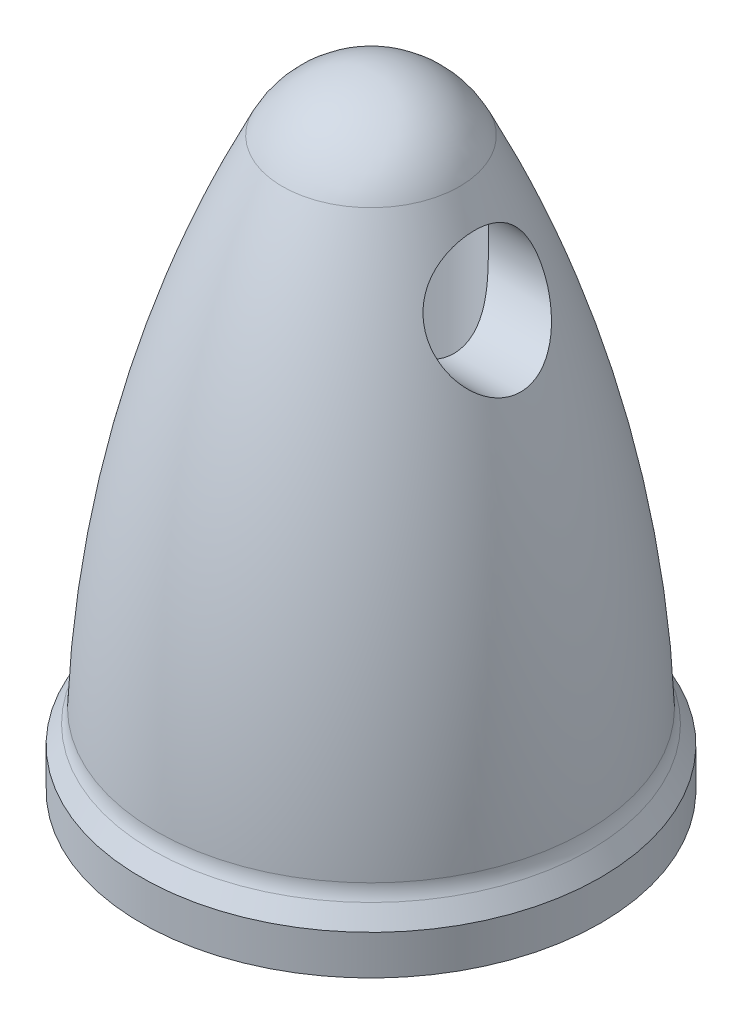
SolidWorks part; units mm, degrees
material "6061 Alloy"
ref_plane "Front Plane" through (0, 0, 0) normal (0, 0, 1) x (1, 0, 0)
ref_plane "Top Plane" through (0, 0, 0) normal (0, 1, 0) x (1, 0, 0)
ref_plane "Right Plane" through (0, 0, 0) normal (1, 0, 0) x (0, 0, -1)
sketch "Sketch1" plane through (0, 0, 0) normal (0, 0, 1) x (1, 0, 0)
  line L0 (0, 0) -> (0, 16.002)
  line L1 (0, 16.002) -> (0, 24.9626) construction
  line L2 (5.5245, 1.651) -> (5.9055, 1.016)
  line L3 (5.9055, 1.016) -> (5.9055, 0)
  line L4 (5.9055, 0) -> (0, 0)
  line L5 (0, 16.002) -> (-8.9606, 16.002) construction
  arc A0 (0, 16.002) -> (2.2789, 14.5838) centre (0, 13.462) cw
  arc A1 (2.2789, 14.5838) -> (5.5245, 1.651) centre (-26.2068, 0.5613) cw
  dimension "D6" = 2.54
  dimension "D7" = 31.75
  dimension "D1" = 16.002
  dimension "D2" = 11.811
  dimension "D3" = 1.016
  dimension "D4" = 11.049
  dimension "D5" = 1.651
revolve "Revolve1" add sketch "Sketch1" angle 360 about L1
sketch "Sketch2" plane through (0, 0, 0) normal (0, -1, 0) x (1, 0, 0)
  circle A0 centre (0, 0) radius 2.1336
  dimension "D1" = 4.2672
extrude "Cut-Extrude1" cut sketch "Sketch2" against normal blind 14.224
chamfer "Chamfer1" distance 2.032 angle 30 1 edges at (2.1336, 14.224, 0)
sketch "Sketch3" plane through (0, 0, 0) normal (1, 0, 0) x (0, 0, -1)
  line L0 (-5.9055, 0) -> (5.9055, 0) construction
  circle A0 centre (0, 12.2936) radius 1.4986
  dimension "D1" = 2.9972
  dimension "D2" = 10.795
extrude "Cut-Extrude2" cut sketch "Sketch3" against normal through all and the other way through all
fillet "Fillet1" radius 0.762 1 edges at (5.5245, 1.651, 0)
